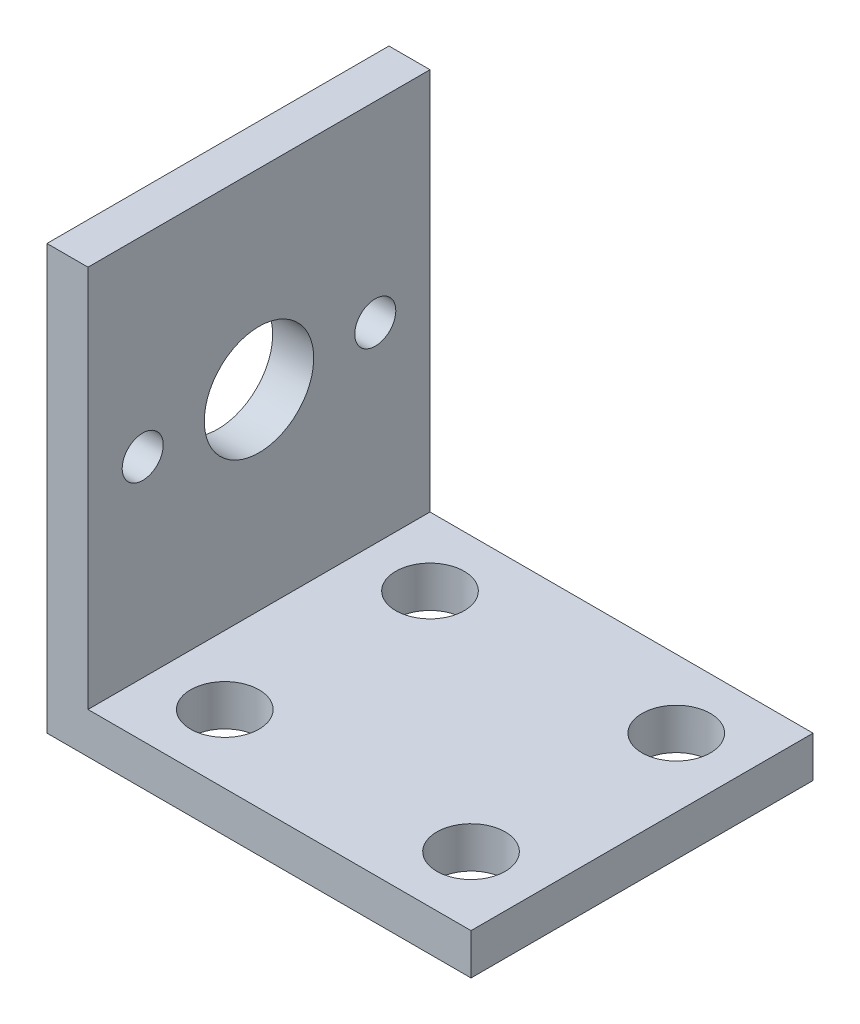
SolidWorks part; units mm, degrees
ref_plane "Front Plane" through (0, 0, 0) normal (0, 0, 1) x (1, 0, 0)
ref_plane "Top Plane" through (0, 0, 0) normal (0, 1, 0) x (1, 0, 0)
ref_plane "Right Plane" through (0, 0, 0) normal (1, 0, 0) x (0, 0, -1)
sketch "Sketch1" plane through (0, 0, 0) normal (0, 0, 1) x (1, 0, 0)
  line L1 (0, 0) -> (31, 0)
  line L2 (0, 0) -> (0, 31)
  line L3 (0, 31) -> (31, 31)
  line L4 (31, 0) -> (31, 31)
  line L5 (31, 31) -> (3, 31)
  line L6 (31, 31) -> (31, 3)
  line L7 (31, 3) -> (3, 3)
  line L8 (3, 31) -> (3, 3)
  dimension "D1" = 31
  dimension "D2" = 31
  dimension "D3" = 3
  dimension "D4" = 3
extrude "Boss-Extrude1" add sketch "Sketch1" along normal blind 25 contours L8 L3 L2 L1 L4 L7
sketch "Sketch2" plane through (3, 0, 0) normal (1, 0, 0) x (0, 0, -1)
  line L0 (-25, 31) -> (0, 3) construction
  line L1 (-25, 17) -> (0, 17) construction
  line L4 (0, 3) -> (0, 31)
  line L5 (0, 31) -> (-25, 31)
  line L6 (-25, 31) -> (-25, 3)
  line L7 (-25, 3) -> (0, 3)
  line L8 (0, 3) -> (0, 31)
  line L9 (0, 31) -> (-25, 31)
  line L10 (-25, 31) -> (-25, 3)
  line L11 (-25, 3) -> (0, 3)
  circle A0 centre (-12.5, 17) radius 4
  circle A1 centre (-21, 17) radius 1.5
  circle A2 centre (-4, 17) radius 1.5
  dimension "D4" = 8
  dimension "D5" = 3
  dimension "D6" = 3
  dimension "D2" = 17
  dimension "D3" = 8.5
  dimension "D1" = 0
extrude "Cut-Extrude1" cut sketch "Sketch2" against normal through all contours A1 | A0 | A2
sketch "Sketch3" plane through (0, 3, 0) normal (0, 1, 0) x (1, 0, 0)
  line L4 (31, 0) -> (3, 0)
  line L5 (3, 0) -> (3, -25)
  line L6 (3, -25) -> (31, -25)
  line L7 (31, -25) -> (31, 0)
  line L8 (31, 0) -> (3, 0)
  line L9 (3, 0) -> (3, -25)
  line L10 (3, -25) -> (31, -25)
  line L11 (31, -25) -> (31, 0)
  line L20 (26, -5) -> (8, -5)
  line L21 (8, -5) -> (8, -20)
  line L22 (8, -20) -> (26, -20)
  line L23 (26, -20) -> (26, -5)
  line L24 (26, -5) -> (8, -5) construction
  line L25 (8, -5) -> (8, -20) construction
  line L26 (8, -20) -> (26, -20) construction
  line L27 (26, -20) -> (26, -5) construction
  circle A0 centre (8, -5) radius 2.5
  circle A1 centre (26, -5) radius 2.5
  circle A2 centre (26, -20) radius 2.5
  circle A3 centre (8, -20) radius 2.5
  dimension "D5" = 5
  dimension "D1" = 0
  dimension "D2" = 5
extrude "Cut-Extrude2" cut sketch "Sketch3" against normal up to next contours A0 | A1 | A2 | A3
